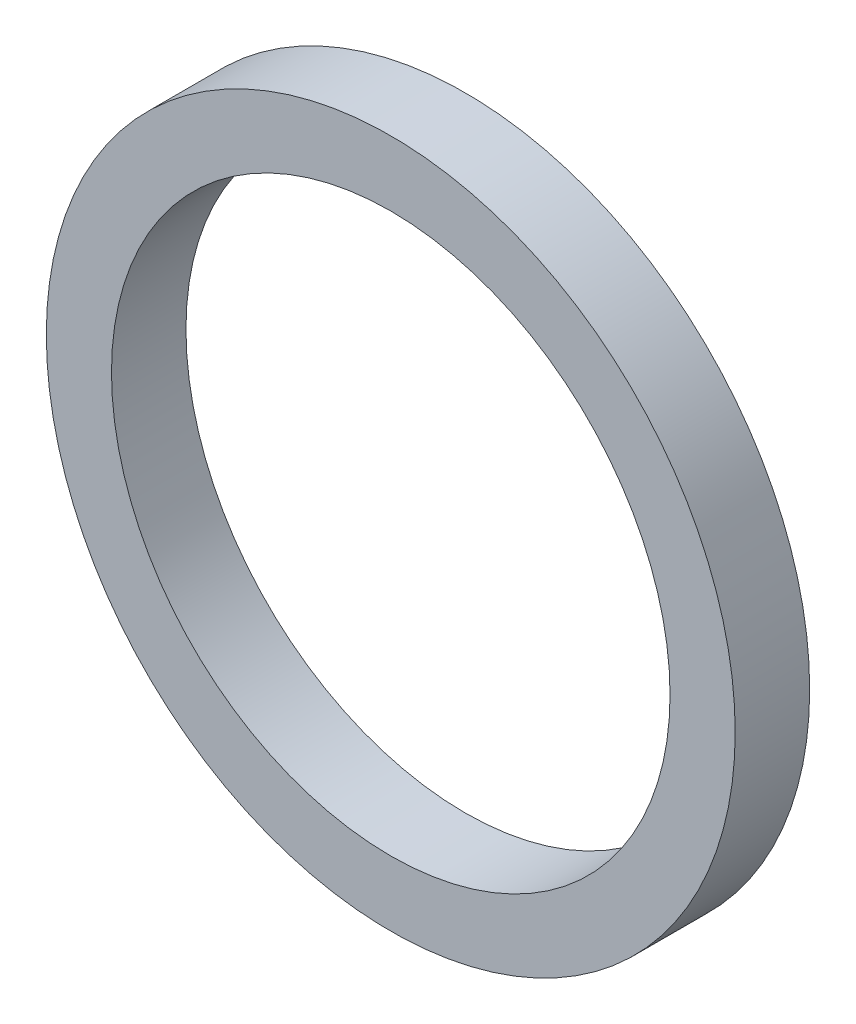
SolidWorks part; units mm, degrees
ref_plane "Front" through (0, 0, 0) normal (0, 0, 1) x (1, 0, 0)
ref_plane "Top" through (0, 0, 0) normal (0, 1, 0) x (1, 0, 0)
ref_plane "Right" through (0, 0, 0) normal (1, 0, 0) x (0, 0, -1)
sketch "Sketch1" plane through (0, 0, 0) normal (0, 0, 1) x (1, 0, 0)
  circle A0 centre (0, 0) radius 18.5
  circle A1 centre (0, 0) radius 15
  dimension "D1" = 30
  dimension "D2" = 37
extrude "Boss-Extrude1" add sketch "Sketch1" along normal blind 4
